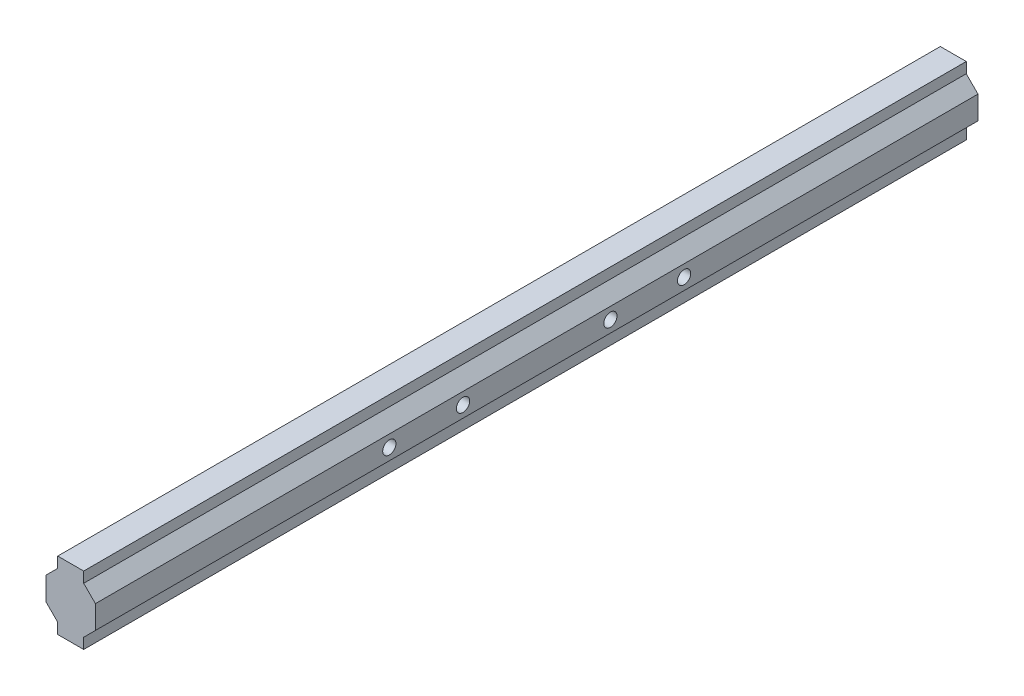
SolidWorks part; units mm, degrees
ref_plane "Front Plane" through (0, 0, 0) normal (0, 0, 1) x (1, 0, 0)
ref_plane "Top Plane" through (0, 0, 0) normal (0, 1, 0) x (1, 0, 0)
ref_plane "Right Plane" through (0, 0, 0) normal (1, 0, 0) x (0, 0, -1)
sketch "Sketch1" plane through (0, 0, 116.1066) normal (0, 0, 1) x (1, 0, 0)
  line L0 (-39.5503, 5.2942) -> (-36.8896, 7.9549)
  line L1 (-36.8896, 7.9549) -> (-36.8896, 10.362)
  line L2 (-36.8896, 10.362) -> (-31.011, 10.362)
  line L3 (-31.011, 7.9549) -> (-28.3503, 5.2942)
  line L4 (-28.3503, 5.2942) -> (-28.3503, 0.0298)
  line L5 (-28.3503, 0.0298) -> (-31.011, -2.6309)
  line L6 (-31.011, -2.6309) -> (-31.011, -5.038)
  line L7 (-31.011, -5.038) -> (-36.8896, -5.038)
  line L8 (-36.8896, -5.038) -> (-36.8896, -2.6309)
  line L9 (-36.8896, -2.6309) -> (-39.5503, 0.0298)
  line L10 (-39.5503, 0.0298) -> (-39.5503, 5.2942)
  line L11 (-31.011, 10.362) -> (-31.011, 7.9549)
  line L12 (-37.3896, 10.862) -> (-30.511, 10.862) construction
  line L13 (-37.3896, -5.538) -> (-30.511, -5.538) construction
  line L14 (-27.8503, 5.4185) -> (-27.8503, -0.0945) construction
  line L15 (-40.0503, 5.4185) -> (-40.0503, -0.0945) construction
  line L16 (-39.9917, 5.5599) -> (-37.3896, 8.162) construction
  line L17 (-37.3896, 8.162) -> (-37.3896, 10.862) construction
  line L18 (-30.511, 8.162) -> (-30.511, 10.862) construction
  line L19 (-27.9089, 5.5599) -> (-30.511, 8.162) construction
  line L20 (-27.9089, -0.2359) -> (-30.511, -2.838) construction
  line L21 (-30.511, -2.838) -> (-30.511, -5.538) construction
  line L22 (-37.3896, -2.838) -> (-37.3896, -5.538) construction
  line L23 (-39.9917, -0.2359) -> (-37.3896, -2.838) construction
  point P24 (-37.3896, 9.512)
  dimension "D1" = 0.5
  dimension "D2" = 0.5
  dimension "D3" = 0.5
  dimension "D4" = 0.5
  dimension "D5" = 0.5
  dimension "D6" = 0.5
  dimension "D7" = 0.5
  dimension "D8" = 0.5
  dimension "D9" = 0.5
  dimension "D10" = 0.5
  dimension "D11" = 0.5
  dimension "D12" = 0.5
extrude "Boss-Extrude1" add sketch "Sketch1" along normal blind 200
sketch "Sketch2" plane through (-28.3503, 0, 0) normal (1, 0, 0) x (0, 0, -1)
  line L0 (-316.1066, 5.2942) -> (-116.1066, 5.2942) construction
  line L1 (-316.1066, 0.0298) -> (-316.1066, 5.2942) construction
  line L3 (-216.1066, 5.2942) -> (-216.1066, -8.2415) construction
  circle A0 centre (-232.8066, 2.662) radius 1.5
  circle A1 centre (-249.5066, 2.662) radius 1.5
  circle A2 centre (-199.4066, 2.662) radius 1.5
  circle A3 centre (-182.7066, 2.662) radius 1.5
  point P6 (-216.1066, 5.2942)
  point P9 (-316.1066, 2.662)
  dimension "D1" = 16.7
  dimension "D2" = 3
  dimension "D3" = 3
  dimension "D4" = 16.7
  dimension "D5" = 0
  dimension "D6" = 0
extrude "Cut-Extrude1" cut sketch "Sketch2" against normal blind 20
